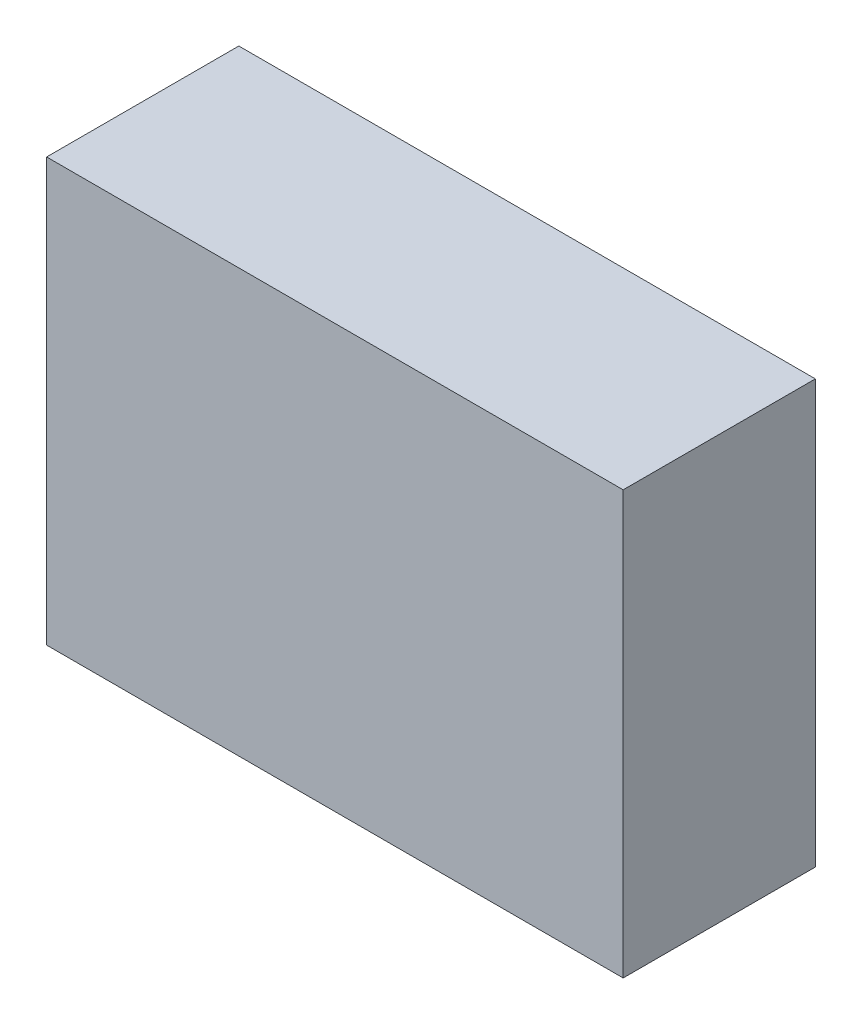
SolidWorks part; units mm, degrees
ref_plane "Front Plane" through (0, 0, 0) normal (0, 0, 1) x (1, 0, 0)
ref_plane "Top Plane" through (0, 0, 0) normal (0, 1, 0) x (1, 0, 0)
ref_plane "Right Plane" through (0, 0, 0) normal (1, 0, 0) x (0, 0, -1)
sketch "Sketch1" plane through (0, 0, 0) normal (0, 0, 1) x (1, 0, 0)
  line L1 (-15, 11) -> (15, 11)
  line L2 (-15, 11) -> (-15, -11)
  line L3 (-15, -11) -> (15, -11)
  line L4 (15, 11) -> (15, -11)
  line L5 (-15, 11) -> (15, -11) construction
  line L6 (-15, -11) -> (15, 11) construction
  point P0 (0, 0)
extrude "Boss-Extrude1" add sketch "Sketch1" against normal blind 10
